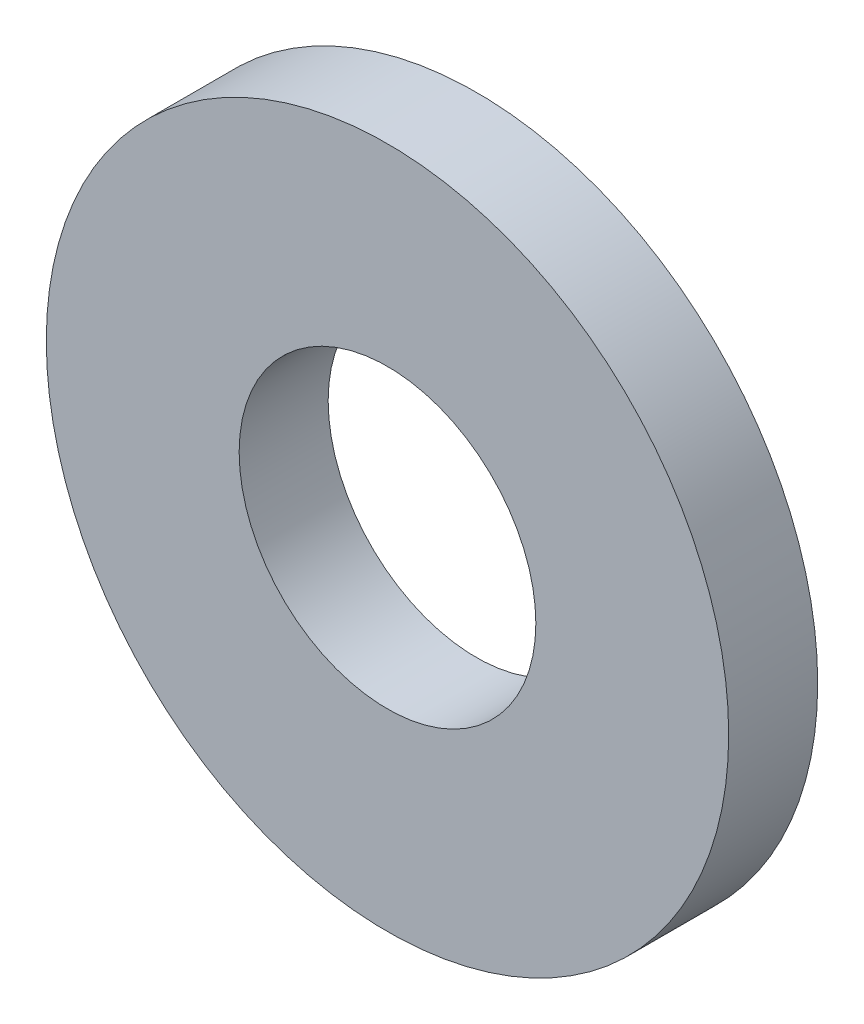
SolidWorks part; units mm, degrees
ref_plane "前视基准面" through (0, 0, 0) normal (0, 0, 1) x (1, 0, 0)
ref_plane "上视基准面" through (0, 0, 0) normal (0, 1, 0) x (1, 0, 0)
ref_plane "右视基准面" through (0, 0, 0) normal (1, 0, 0) x (0, 0, -1)
sketch "草图1" plane through (0, 0, 0) normal (0, 0, 1) x (1, 0, 0)
  line L0 (8, -3.1754) -> (10.75, -1.5877)
  line L1 (3.1754, 8) -> (1.5877, 10.75)
  line L2 (1.5877, 10.75) -> (-1.5877, 10.75)
  line L3 (-1.5877, 10.75) -> (-3.1754, 8)
  line L4 (-3.1754, 8) -> (-1.5877, 5.25)
  line L5 (-1.5877, 5.25) -> (1.5877, 5.25)
  line L6 (1.5877, 5.25) -> (3.1754, 8)
  line L7 (10.75, -1.5877) -> (10.75, 1.5877)
  line L8 (10.75, 1.5877) -> (8, 3.1754)
  line L9 (8, 3.1754) -> (5.25, 1.5877)
  line L10 (5.25, 1.5877) -> (5.25, -1.5877)
  line L11 (5.25, -1.5877) -> (8, -3.1754)
  line L12 (-3.1754, -8) -> (-1.5877, -10.75)
  line L13 (-1.5877, -10.75) -> (1.5877, -10.75)
  line L14 (1.5877, -10.75) -> (3.1754, -8)
  line L15 (3.1754, -8) -> (1.5877, -5.25)
  line L16 (1.5877, -5.25) -> (-1.5877, -5.25)
  line L17 (-1.5877, -5.25) -> (-3.1754, -8)
  line L18 (-8, 3.1754) -> (-10.75, 1.5877)
  line L19 (-10.75, 1.5877) -> (-10.75, -1.5877)
  line L20 (-10.75, -1.5877) -> (-8, -3.1754)
  line L21 (-8, -3.1754) -> (-5.25, -1.5877)
  line L22 (-5.25, -1.5877) -> (-5.25, 1.5877)
  line L23 (-5.25, 1.5877) -> (-8, 3.1754)
  circle A0 centre (0, 0) radius 11.5
  circle A1 centre (0, 0) radius 8 construction
  circle A2 centre (0, 8) radius 2.75 construction
  point P33 (0, 0)
  dimension "D1" = 4
extrude "凸台-拉伸1" add sketch "草图1" along normal blind 2.3
sketch "草图2" plane through (0, 0, 2.3) normal (0, 0, 1) x (1, 0, 0)
  circle A0 centre (0, 0) radius 11.5
extrude "凸台-拉伸2" add sketch "草图2" along normal blind 0.7
sketch "草图3" plane through (0, 0, 3) normal (0, 0, 1) x (1, 0, 0)
  circle A0 centre (0, 0) radius 5
extrude "切除-拉伸1" cut sketch "草图3" against normal blind 10
